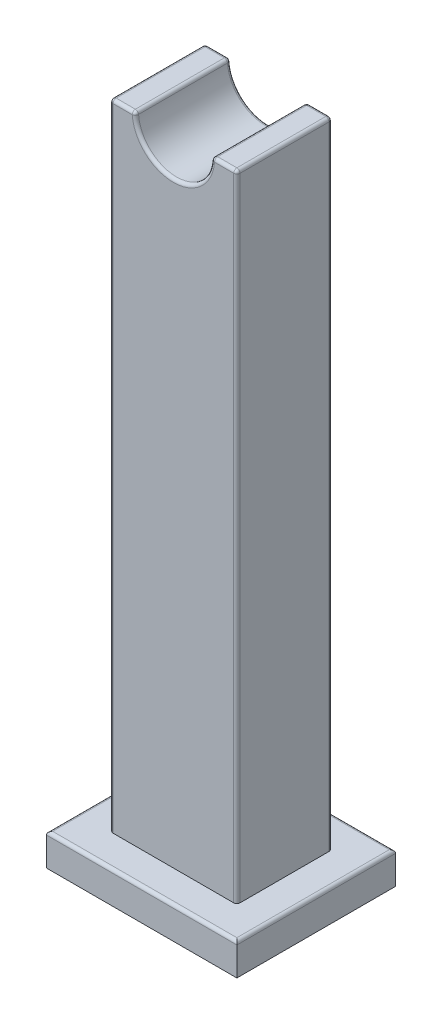
SolidWorks part; units mm, degrees
ref_plane "Plan de face" through (0, 0, 0) normal (0, 0, 1) x (1, 0, 0)
ref_plane "Plan de dessus" through (0, 0, 0) normal (0, 1, 0) x (1, 0, 0)
ref_plane "Plan de droite" through (0, 0, 0) normal (1, 0, 0) x (0, 0, -1)
sketch "Esquisse1" plane through (0, 0, 0) normal (0, 0, 1) x (1, 0, 0)
  line L0 (6, 0) -> (10, 0)
  line L1 (-10, 0) -> (-6, 0)
  line L2 (-10, 0) -> (-10, -100)
  line L3 (-10, -100) -> (10, -100)
  line L4 (10, 0) -> (10, -100)
  arc A0 (-6, 0) -> (6, 0) centre (0, 0) ccw
  dimension "D1" = 12
  dimension "D2" = 20
  dimension "D3" = 10
  dimension "D4" = 100
extrude "Boss.-Extru.1" add sketch "Esquisse1" along normal blind 15
sketch "Esquisse2" plane through (0, -100, 0) normal (0, -1, 0) x (1, 0, 0)
  line L0 (-10, 0) -> (10, 0) construction
  line L1 (-15, 20) -> (15, 20)
  line L2 (-15, 20) -> (-15, -5)
  line L3 (-15, -5) -> (15, -5)
  line L4 (15, 20) -> (15, -5)
  line L5 (-10, 15) -> (-10, 0) construction
  dimension "D1" = 25
  dimension "D2" = 5
  dimension "D3" = 30
  dimension "D4" = 5
extrude "Boss.-Extru.2" add sketch "Esquisse2" along normal blind 5
fillet "Congé1" radius 0.5 18 edges at (-10, -50, 0) (8, 0, 0) (-8, 0, 15) (-8, 0, 0) (-10, 0, 7.5) (-6, 0, 7.5) (0, -6, 0) (6, 0, 7.5) (0, -6, 15) (10, 0, 7.5) (8, 0, 15) (-10, -50, 15) (-15, -100, 7.5) (0, -100, -5) (10, -50, 0) (10, -50, 15) (15, -100, 7.5) (0, -100, 20)
